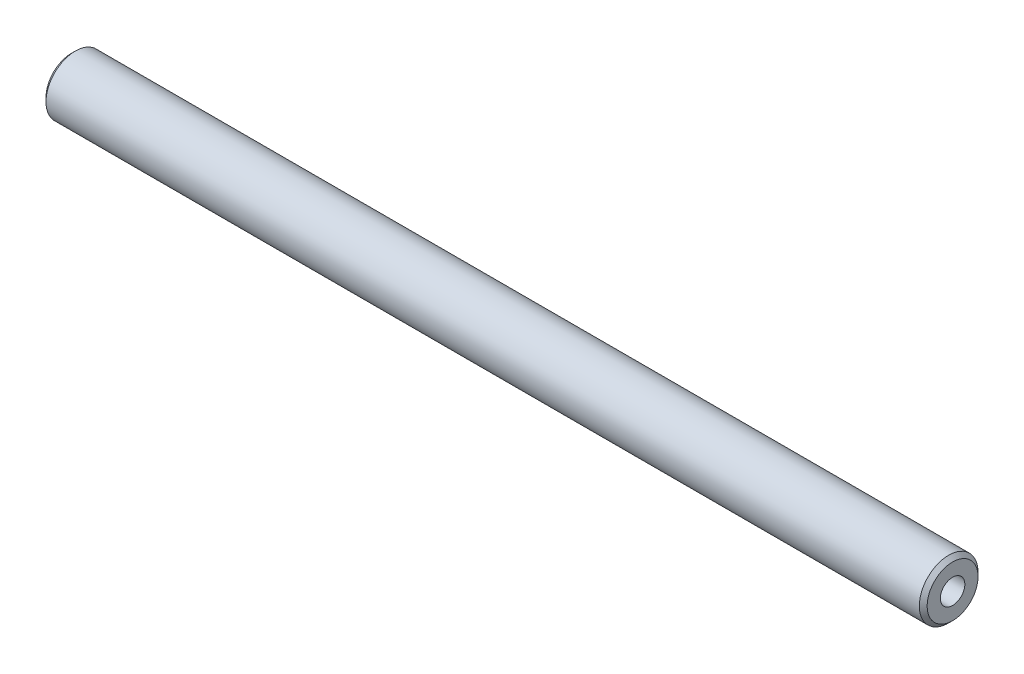
SolidWorks part; units mm, degrees
material "A2017-T4"
ref_plane "Front Plane" through (0, 0, 0) normal (0, 0, 1) x (1, 0, 0)
ref_plane "Top Plane" through (0, 0, 0) normal (0, 1, 0) x (1, 0, 0)
ref_plane "Right Plane" through (0, 0, 0) normal (1, 0, 0) x (0, 0, -1)
sketch "Sketch1" plane through (0, 0, 0) normal (0, 0, 1) x (1, 0, 0)
  line L0 (0, 3) -> (90, 3)
  line L1 (0, 0) -> (90, 0)
  line L2 (0, 3) -> (0, 0)
  line L3 (0, 0) -> (90, 0) construction
  line L4 (90, 3) -> (90, 0)
  dimension "L" = 90
  dimension "D" = 6
revolve "Revolve1" add sketch "Sketch1" angle 360 about L1
chamfer "Chamfer1" distance 0.4 angle 45 2 edges at (90, 0, 3) (0, 0, 3)
ref_plane "Dim. SC" through (6, 0, 0) normal (1, 0, 0) x (0, 0, -1)
hole_wizard "Tapped Hole1" [suppressed] positions "Sketch3" profile "Sketch2" tap size "M4x0.7" standard "JIS"
sketch "Sketch3" [suppressed] plane through (0, 0, 0) normal (-1, 0, 0) x (0, 0, 1)
  point P0 (0, 0)
sketch "Sketch2" [suppressed] plane through (0, 0, 0) normal (0, 1, 0) x (0, 0, 1)
  line L0 (0, 0) -> (0, 12.4914)
  line L1 (0, 12.4914) -> (1.65, 11.5)
  line L2 (1.65, 11.5) -> (1.65, 0)
  line L3 (2, 0) -> (2, 11.5) construction
  line L5 (1.65, 0) -> (0, 0)
  line L10 (0, 12.4914) -> (-1.65, 11.5) construction
  line L11 (0, 0) -> (0, 12.4914) construction
  dimension "Tap Drill Dia." = 3.3
  dimension "Tap Drill Depth" = 11.5
  dimension "Drill Angle" = 118
  dimension "M" = 3
cosmetic thread "Hole Thread1" [suppressed] parameters "Mx2"=8, "M"=3
hole_wizard "Tapped Hole2" [suppressed] positions "Sketch5" profile "Sketch4" tap size "M4x0.7" standard "JIS"
sketch "Sketch5" [suppressed] plane through (30, 0, 0) normal (1, 0, 0) x (0, 0, -1)
  point P0 (0, 0)
sketch "Sketch4" [suppressed] plane through (30, 0, 0) normal (0, 1, 0) x (0, 0, -1)
  line L0 (0, 0) -> (0, 12.4914)
  line L1 (0, 12.4914) -> (1.65, 11.5)
  line L2 (1.65, 11.5) -> (1.65, 0)
  line L5 (1.65, 0) -> (0, 0)
  line L10 (0, 12.4914) -> (-1.65, 11.5) construction
  line L11 (0, 0) -> (0, 12.4914) construction
  dimension "Tap Drill Dia." = 3.3
  dimension "Tap Drill Depth" = 11.5
  dimension "Drill Angle" = 118
cosmetic thread "Hole Thread2" [suppressed] parameters "Mx2"=8, "M"=3
hole_wizard "Tapped Hole3" [suppressed] positions "Sketch7" profile "Sketch6" tap size "M4x0.7" standard "JIS"
sketch "Sketch7" [suppressed] plane through (0, 0, 0) normal (-1, 0, 0) x (0, 0, 1)
  point P0 (0, 0)
sketch "Sketch6" [suppressed] plane through (0, 0, 0) normal (0, 1, 0) x (0, 0, 1)
  line L0 (0, 0) -> (0, 30)
  line L1 (0, 30) -> (1.65, 30)
  line L2 (1.65, 30) -> (1.65, 0)
  line L5 (1.65, 0) -> (0, 0)
  line L11 (0, 0) -> (0, 30) construction
  dimension "Thru Tap Drill Dia." = 3.3
  dimension "Thru Tap Drill Depth" = 30
cosmetic thread "Hole Thread3" [suppressed] parameters "M"=3
sketch "Sketch8" [suppressed] plane through (0, 0, 0) normal (0, 1, 0) x (1, 0, 0)
  line L0 (10, -3.5) -> (10, -4) construction
  line L1 (6, 4) -> (14, 4)
  line L2 (6, 4) -> (6, 3.5)
  line L3 (6, 3.5) -> (14, 3.5)
  line L4 (14, 4) -> (14, 3.5)
  line L5 (6, -3.5) -> (14, -3.5)
  line L6 (6, -3.5) -> (6, -4)
  line L7 (6, -4) -> (14, -4)
  line L8 (14, -3.5) -> (14, -4)
  line L12 (0, 0) -> (30, 0) construction
  dimension "S" = 6
  dimension "W" = 7
  dimension "L1_s" = 8
  dimension "D" = 6
  dimension "L1_s_L" = 8
extrude "Cut-Extrude1" [suppressed] cut sketch "Sketch8" against normal through all and the other way through all
ref_plane "L Dimension Selectable_SEC" [suppressed] through (10, 0, 0) normal (1, 0, 0) x (0, 0, -1)
hole_wizard "Tapped Hole4" [suppressed] positions "Sketch10" profile "Sketch9" tap size "M4x0.7" standard "JIS"
sketch "Sketch10" [suppressed] plane through (0, 0, 0) normal (-1, 0, 0) x (0, 0, 1)
  point P0 (0, 0)
sketch "Sketch9" [suppressed] plane through (0, 0, 0) normal (0, 1, 0) x (0, 0, 1)
  line L0 (0, 0) -> (0, 12.4914)
  line L1 (0, 12.4914) -> (1.65, 11.5)
  line L2 (1.65, 11.5) -> (1.65, 0)
  line L3 (2, 0) -> (2, 11.5) construction
  line L5 (1.65, 0) -> (0, 0)
  line L10 (0, 12.4914) -> (-1.65, 11.5) construction
  line L11 (0, 0) -> (0, 12.4914) construction
  dimension "Tap Drill Dia." = 3.3
  dimension "Tap Drill Depth" = 11.5
  dimension "Drill Angle" = 118
  dimension "M" = 3
cosmetic thread "Hole Thread4" [suppressed] parameters "Mx2"=8, "M"=3
hole_wizard "Tapped Hole5" [suppressed] positions "Sketch12" profile "Sketch11" tap size "M4x0.7" standard "JIS"
sketch "Sketch12" [suppressed] plane through (30, 0, 0) normal (1, 0, 0) x (0, 0, -1)
  point P0 (0, 0)
sketch "Sketch11" [suppressed] plane through (30, 0, 0) normal (0, 1, 0) x (0, 0, -1)
  line L0 (0, 0) -> (0, 12.4914)
  line L1 (0, 12.4914) -> (1.65, 11.5)
  line L2 (1.65, 11.5) -> (1.65, 0)
  line L5 (1.65, 0) -> (0, 0)
  line L10 (0, 12.4914) -> (-1.65, 11.5) construction
  line L11 (0, 0) -> (0, 12.4914) construction
  dimension "Tap Drill Dia." = 3.3
  dimension "Tap Drill Depth" = 11.5
  dimension "Drill Angle" = 118
cosmetic thread "Hole Thread5" [suppressed] parameters "Mx2"=8, "M"=3
hole_wizard "Tapped Hole6" [suppressed] positions "Sketch14" profile "Sketch13" tap size "M4x0.7" standard "JIS"
sketch "Sketch14" [suppressed] plane through (0, 0, 0) normal (-1, 0, 0) x (0, 0, 1)
  point P0 (0, 0)
sketch "Sketch13" [suppressed] plane through (0, 0, 0) normal (0, 1, 0) x (0, 0, 1)
  line L0 (0, 0) -> (0, 30)
  line L1 (0, 30) -> (1.65, 30)
  line L2 (1.65, 30) -> (1.65, 0)
  line L5 (1.65, 0) -> (0, 0)
  line L11 (0, 0) -> (0, 30) construction
  dimension "Thru Tap Drill Dia." = 3.3
  dimension "Thru Tap Drill Depth" = 30
cosmetic thread "Hole Thread6" [suppressed] parameters "M"=3
hole_wizard "Tapped Hole7" [suppressed] positions "Sketch16" profile "Sketch15" tap size "M4x0.7" standard "JIS"
sketch "Sketch16" [suppressed] plane through (0, 0, 0) normal (-1, 0, 0) x (0, 0, 1)
  point P0 (0, 0)
sketch "Sketch15" [suppressed] plane through (0, 0, 0) normal (0, 1, 0) x (0, 0, 1)
  line L0 (0, 0) -> (0, 12.4914)
  line L1 (0, 12.4914) -> (1.65, 11.5)
  line L2 (1.65, 11.5) -> (1.65, 0)
  line L3 (2, 0) -> (2, 11.5) construction
  line L5 (1.65, 0) -> (0, 0)
  line L10 (0, 12.4914) -> (-1.65, 11.5) construction
  line L11 (0, 0) -> (0, 12.4914) construction
  dimension "Tap Drill Dia." = 3.3
  dimension "Tap Drill Depth" = 11.5
  dimension "Drill Angle" = 118
  dimension "M" = 3
cosmetic thread "Hole Thread7" [suppressed] parameters "Mx2"=8, "M"=3
hole_wizard "Tapped Hole8" [suppressed] positions "Sketch18" profile "Sketch17" tap size "M4x0.7" standard "JIS"
sketch "Sketch18" [suppressed] plane through (30, 0, 0) normal (1, 0, 0) x (0, 0, -1)
  point P0 (0, 0)
sketch "Sketch17" [suppressed] plane through (30, 0, 0) normal (0, 1, 0) x (0, 0, -1)
  line L0 (0, 0) -> (0, 12.4914)
  line L1 (0, 12.4914) -> (1.65, 11.5)
  line L2 (1.65, 11.5) -> (1.65, 0)
  line L5 (1.65, 0) -> (0, 0)
  line L10 (0, 12.4914) -> (-1.65, 11.5) construction
  line L11 (0, 0) -> (0, 12.4914) construction
  dimension "Tap Drill Dia." = 3.3
  dimension "Tap Drill Depth" = 11.5
  dimension "Drill Angle" = 118
cosmetic thread "Hole Thread8" [suppressed] parameters "Mx2"=8, "M"=3
hole_wizard "Tapped Hole9" [suppressed] positions "Sketch20" profile "Sketch19" tap size "M4x0.7" standard "JIS"
sketch "Sketch20" [suppressed] plane through (0, 0, 0) normal (-1, 0, 0) x (0, 0, 1)
  point P0 (0, 0)
sketch "Sketch19" [suppressed] plane through (0, 0, 0) normal (0, 1, 0) x (0, 0, 1)
  line L0 (0, 0) -> (0, 30)
  line L1 (0, 30) -> (1.65, 30)
  line L2 (1.65, 30) -> (1.65, 0)
  line L5 (1.65, 0) -> (0, 0)
  line L11 (0, 0) -> (0, 30) construction
  dimension "Thru Tap Drill Dia." = 3.3
  dimension "Thru Tap Drill Depth" = 30
cosmetic thread "Hole Thread9" [suppressed] parameters "M"=3
sketch "Sketch21" [suppressed] plane through (0, 0, 0) normal (0, 1, 0) x (1, 0, 0)
  line L0 (0, 0) -> (30, 0) construction
  line L1 (6, 4) -> (14, 4)
  line L2 (6, 4) -> (6, 3.5)
  line L3 (6, 3.5) -> (14, 3.5)
  line L4 (14, 4) -> (14, 3.5)
  line L5 (6, -3.5) -> (14, -3.5)
  line L6 (6, -3.5) -> (6, -4)
  line L7 (6, -4) -> (14, -4)
  line L8 (14, -3.5) -> (14, -4)
  line L9 (10, -3.5) -> (10, -4) construction
  line L18 (6, -4.4) -> (6, 4.4) construction
  line L19 (30, -3.6) -> (30, 3.6) construction
  dimension "W" = 7
  dimension "L1_s" = 8
  dimension "D" = 6
  dimension "L1_s_L" = 8
extrude "Cut-Extrude2" [suppressed] cut sketch "Sketch21" against normal through all and the other way through all
ref_plane "L Dimension Cofigurable, Wrench Flats_SEC" [suppressed] through (10, 0, 0) normal (1, 0, 0) x (0, 0, -1)
hole_wizard "Tapped Hole10" positions "Sketch23" profile "Sketch22" tap size "M4x0.7" standard "JIS"
sketch "Sketch23" plane through (0, 0, 0) normal (-1, 0, 0) x (0, 0, 1)
  point P0 (0, 0)
sketch "Sketch22" plane through (0, 0, 0) normal (0, 1, 0) x (0, 0, 1)
  line L0 (0, 0) -> (0, 9.2511)
  line L1 (0, 9.2511) -> (1.25, 8.5)
  line L2 (1.25, 8.5) -> (1.25, 0)
  line L3 (1.5, 0) -> (1.5, 8.5) construction
  line L5 (1.25, 0) -> (0, 0)
  line L10 (0, 9.2511) -> (-1.25, 8.5) construction
  line L11 (0, 0) -> (0, 9.2511) construction
  dimension "Tap Drill Dia." = 2.5
  dimension "Tap Drill Depth" = 8.5
  dimension "Drill Angle" = 118
  dimension "M" = 3
  dimension "Pilot hole Tip" = 9.2511
cosmetic thread "Hole Thread10" parameters "Mx2"=6, "M"=3
hole_wizard "Tapped Hole11" positions "Sketch25" profile "Sketch24" tap size "M4x0.7" standard "JIS"
sketch "Sketch25" plane through (90, 0, 0) normal (1, 0, 0) x (0, 0, -1)
  point P0 (0, 0)
sketch "Sketch24" plane through (90, 0, 0) normal (0, 1, 0) x (0, 0, -1)
  line L0 (0, 9.2511) -> (0, 0)
  line L1 (0, 9.2511) -> (1.25, 8.5)
  line L2 (1.25, 8.5) -> (1.25, 0)
  line L3 (1.5, 8.5) -> (1.5, 0) construction
  line L5 (1.25, 0) -> (0, 0)
  line L10 (0, 9.2511) -> (-1.25, 8.5) construction
  line L11 (0, 0) -> (0, 9.2511) construction
  dimension "Tap Drill Dia." = 2.5
  dimension "Tap Drill Depth" = 8.5
  dimension "Drill Angle" = 118
  dimension "N" = 3
  dimension "Pilot hole Tip" = 9.2511
cosmetic thread "Hole Thread11" parameters "Nx2"=6, "N"=3
sketch "Sketch26" plane through (0, 0, 0) normal (-1, 0, 0) x (0, 0, 1)
  circle A0 centre (0, 0) radius 1.25
  circle A1 centre (0, 0) radius 1.25
  dimension "MSM_1" = 2.5
  dimension "MSM_2" = 2.5
extrude "Boss-Extrude1" [suppressed] add sketch "Sketch26" against normal blind 6
sketch "Sketch27" plane through (90, 0, 0) normal (1, 0, 0) x (0, 0, -1)
  circle A0 centre (0, 0) radius 1.25
  circle A1 centre (0, 0) radius 1.25
  dimension "MSM_2" = 2.5
  dimension "MSM_1" = 2.5
extrude "Boss-Extrude2" [suppressed] add sketch "Sketch27" against normal blind 6
hole_wizard "Tapped Hole12" [suppressed] positions "Sketch29" profile "Sketch28" tap size "M4x0.7" standard "JIS"
sketch "Sketch29" [suppressed] plane through (0, 0, 0) normal (-1, 0, 0) x (0, 0, 1)
  point P0 (0, 0)
sketch "Sketch28" [suppressed] plane through (0, 0, 0) normal (0, 1, 0) x (0, 0, 1)
  line L0 (0, 0) -> (0, 12.4914)
  line L1 (0, 12.4914) -> (1.65, 11.5)
  line L2 (1.65, 11.5) -> (1.65, 0)
  line L3 (2, 0) -> (2, 11.5) construction
  line L5 (1.65, 0) -> (0, 0)
  line L10 (0, 12.4914) -> (-1.65, 11.5) construction
  line L11 (0, 0) -> (0, 12.4914) construction
  dimension "Tap Drill Dia." = 3.3
  dimension "Tap Drill Depth" = 11.5
  dimension "Drill Angle" = 118
  dimension "M" = 3
  dimension "Pilot hole Tip" = 12.4914
cosmetic thread "Hole Thread12" [suppressed] parameters "Mx2"=8, "M"=3
hole_wizard "Tapped Hole13" [suppressed] positions "Sketch31" profile "Sketch30" tap size "M4x0.7" standard "JIS"
sketch "Sketch31" [suppressed] plane through (30, 0, 0) normal (1, 0, 0) x (0, 0, -1)
  point P0 (0, 0)
sketch "Sketch30" [suppressed] plane through (30, 0, 0) normal (0, 1, 0) x (0, 0, -1)
  line L0 (0, 12.4914) -> (0, 0)
  line L1 (0, 12.4914) -> (1.65, 11.5)
  line L2 (1.65, 11.5) -> (1.65, 0)
  line L3 (2, 11.5) -> (2, 0) construction
  line L5 (1.65, 0) -> (0, 0)
  line L10 (0, 12.4914) -> (-1.65, 11.5) construction
  line L11 (0, 0) -> (0, 12.4914) construction
  dimension "Tap Drill Dia." = 3.3
  dimension "Tap Drill Depth" = 11.5
  dimension "Drill Angle" = 118
  dimension "N" = 3
  dimension "Pilot hole Tip" = 12.4914
cosmetic thread "Hole Thread13" [suppressed] parameters "Nx2"=8, "N"=3
sketch "Sketch32" [suppressed] plane through (0, 0, 0) normal (-1, 0, 0) x (0, 0, 1)
  circle A0 centre (0, 0) radius 1.65
  circle A1 centre (0, 0) radius 1.65
  dimension "MSM_2" = 2.5
  dimension "MSM_1" = 2.5
extrude "Boss-Extrude3" [suppressed] add sketch "Sketch32" against normal blind 6
sketch "Sketch33" [suppressed] plane through (30, 0, 0) normal (1, 0, 0) x (0, 0, -1)
  circle A0 centre (0, 0) radius 1.65
  circle A1 centre (0, 0) radius 1.65
  dimension "MSM_1" = 2.5
  dimension "MSM_2" = 2.5
extrude "Boss-Extrude4" [suppressed] add sketch "Sketch33" against normal blind 6
sketch "Sketch34" [suppressed] plane through (0, 0, 0) normal (0, 1, 0) x (1, 0, 0)
  line L0 (10, -3.5) -> (10, -4) construction
  line L1 (6, 4) -> (14, 4)
  line L2 (6, 4) -> (6, 3.5)
  line L3 (6, 3.5) -> (14, 3.5)
  line L4 (14, 4) -> (14, 3.5)
  line L5 (6, -3.5) -> (14, -3.5)
  line L6 (6, -3.5) -> (6, -4)
  line L7 (6, -4) -> (14, -4)
  line L8 (14, -3.5) -> (14, -4)
  line L9 (30, -3.6) -> (30, 3.6) construction
  line L12 (0, 0) -> (30, 0) construction
  line L15 (6, -4.4) -> (6, 4.4) construction
  dimension "L1_s" = 8
  dimension "W" = 7
  dimension "D" = 6
  dimension "L1_s_L" = 8
extrude "Cut-Extrude3" [suppressed] cut sketch "Sketch34" against normal through all and the other way through all
ref_plane "L Dimension Configurable, Thread Dia. Configurable, Wrench Flats_SEC" [suppressed] through (10, 0, 0) normal (1, 0, 0) x (0, 0, -1)
hole_wizard "Tapped Hole14" [suppressed] positions "Sketch36" profile "Sketch35" tap size "M4x0.7" standard "JIS"
sketch "Sketch36" [suppressed] plane through (0, 0, 0) normal (-1, 0, 0) x (0, 0, 1)
  point P0 (0, 0)
sketch "Sketch35" [suppressed] plane through (0, 0, 0) normal (0, 1, 0) x (0, 0, 1)
  line L0 (0, 0) -> (0, 16.4914)
  line L1 (0, 16.4914) -> (1.65, 15.5)
  line L2 (1.65, 15.5) -> (1.65, 0)
  line L5 (1.65, 0) -> (0, 0)
  line L10 (0, 16.4914) -> (-1.65, 15.5) construction
  line L11 (0, 0) -> (0, 16.4914) construction
  dimension "Tap Drill Dia." = 3.3
  dimension "Tap Drill Depth" = 15.5
  dimension "Drill Angle" = 118
cosmetic thread "Hole Thread14" [suppressed] parameters "Mx3"=12, "MD"=4
hole_wizard "Tapped Hole15" [suppressed] positions "Sketch38" profile "Sketch37" tap size "M4x0.7" standard "JIS"
sketch "Sketch38" [suppressed] plane through (30, -2.1135, -9.2544) normal (1, 0, 0) x (0, 0, -1)
  point P0 (-9.2544, 2.1135)
sketch "Sketch37" [suppressed] plane through (30, 0, 0) normal (0, 1, 0) x (0, 0, -1)
  line L0 (0, 0) -> (0, 16.4914)
  line L1 (0, 16.4914) -> (1.65, 15.5)
  line L2 (1.65, 15.5) -> (1.65, 0)
  line L5 (1.65, 0) -> (0, 0)
  line L10 (0, 16.4914) -> (-1.65, 15.5) construction
  line L11 (0, 0) -> (0, 16.4914) construction
  dimension "Tap Drill Dia." = 3.3
  dimension "Tap Drill Depth" = 15.5
  dimension "Drill Angle" = 118
cosmetic thread "Hole Thread15" [suppressed] parameters "Nx3"=12, "ND"=4
ref_plane "Plane1" [suppressed] through (0, 4, 0) normal (0, 1, 0) x (1, 0, 0)
hole_wizard "Diameter Hole1" [suppressed] positions "Sketch40" profile "Sketch39" hole size "Ø2.5" standard "JIS"
sketch "Sketch40" [suppressed] plane through (0, 4, 0) normal (0, 1, 0) x (1, 0, 0)
  line L0 (0, 3.8) -> (0, -3.8) construction
  point P0 (7, 0)
  dimension "HL" = 7
sketch "Sketch39" [suppressed] plane through (7, 4, 0) normal (1, 0, 0) x (0, 0, 1)
  line L0 (0, 0) -> (0, 8)
  line L1 (0, 8) -> (1.25, 8)
  line L2 (1.25, 8) -> (1.25, 0)
  line L5 (1.25, 0) -> (0, 0)
  line L11 (0, 0) -> (0, 8) construction
  dimension "D_s" = 2.5
  dimension "Thru Hole Depth" = 8
equation "\"Plane dim\"= \"D@Sketch1\" * 0.5"
equation "\"D1@Boss-Extrude1\" = \"M\" * 2"
equation "\"D1@Boss-Extrude2\" = \"N\" * 2"
equation "\"D1@Boss-Extrude3\" = \"M\" * 2"
equation "\"D1@Boss-Extrude4\" = \"N\" * 2"
equation "\"M\"=3"
equation "\"N\"=3"
